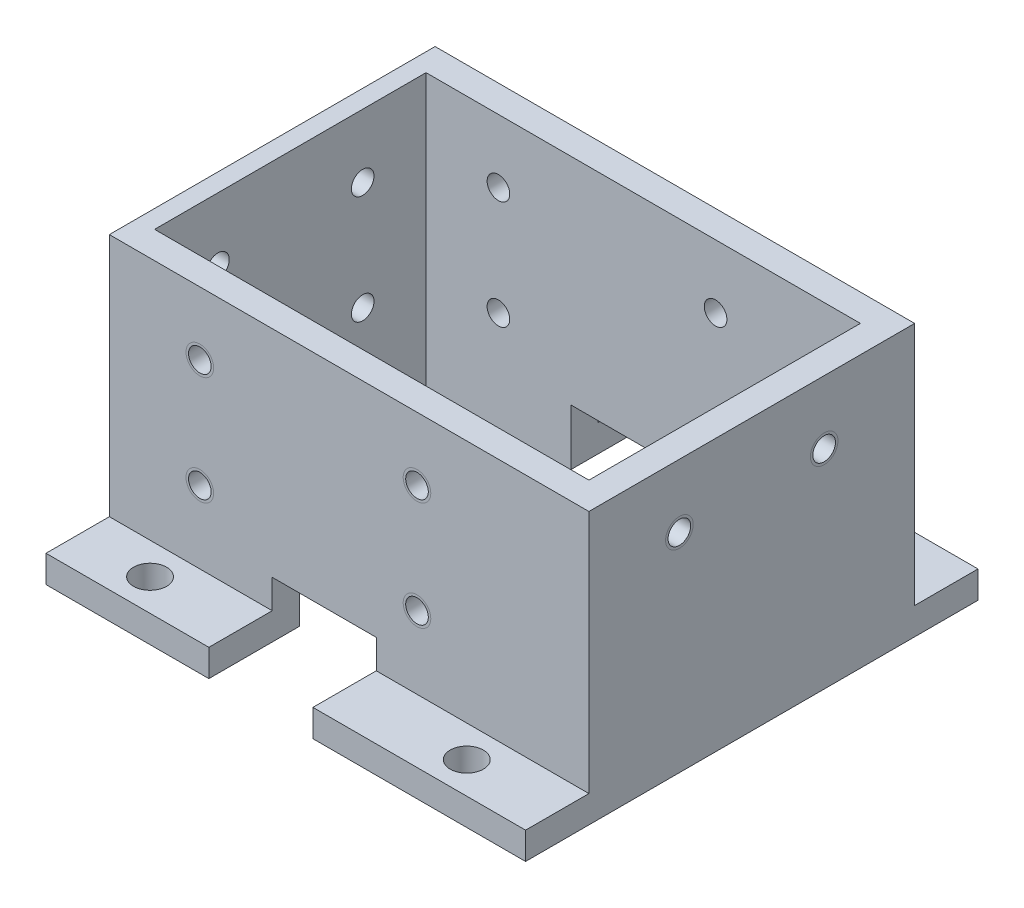
SolidWorks part; units mm, degrees
material "ABS"
ref_plane "Front Plane" through (0, 0, 0) normal (0, 0, 1) x (1, 0, 0)
ref_plane "Top Plane" through (0, 0, 0) normal (0, 1, 0) x (1, 0, 0)
ref_plane "Right Plane" through (0, 0, 0) normal (1, 0, 0) x (0, 0, -1)
sketch "Sketch1" plane through (0, 0, 0) normal (1, 0, 0) x (0, 0, -1)
  line L0 (0, 0) -> (0, 38)
  line L1 (0, 38) -> (36, 38)
  line L2 (36, 38) -> (36, 0)
  line L3 (36, 0) -> (0, 0)
  dimension "D1" = 38
  dimension "D2" = 36
extrude "Boss-Extrude2" add sketch "Sketch1" along normal blind 53
sketch "Sketch3" plane through (53, 0, 0) normal (1, 0, 0) x (0, 0, -1)
  line L0 (36, 0) -> (0, 0) construction
  line L1 (3, 0) -> (3, 35)
  line L2 (3, 35) -> (33, 35)
  line L3 (33, 35) -> (33, 0)
  line L4 (33, 0) -> (3, 0)
  line L5 (0, 38) -> (36, 38) construction
  line L6 (36, 38) -> (36, 0) construction
  line L7 (0, 0) -> (0, 38) construction
  dimension "D1" = 3
  dimension "D2" = 3
  dimension "D3" = 3
extrude "Cut-Extrude1" cut sketch "Sketch3" against normal blind 51
sketch "Sketch4" plane through (0, 0, 0) normal (0, 0, 1) x (1, 0, 0)
  line L0 (50, 0) -> (50, 30)
  line L1 (53, 0) -> (0, 0) construction
  line L2 (50, 30) -> (53, 30)
  line L3 (53, 38) -> (53, 0) construction
  line L4 (53, 30) -> (53, 0)
  line L5 (53, 0) -> (50, 0)
  dimension "D1" = 3
  dimension "D2" = 30
extrude "Boss-Extrude3" add sketch "Sketch4" against normal up to surface (33 mm away) up to face at (27.5, 17.5, -33)
sketch "Sketch5" plane through (0, 0, 0) normal (0, 0, 1) x (1, 0, 0)
  line L0 (53, 30) -> (0, 30)
  line L1 (53, 38) -> (53, 0) construction
  line L2 (0, 30) -> (0, 38)
  line L3 (53, 38) -> (0, 38) construction
  line L4 (0, 38) -> (53, 38)
  line L5 (53, 38) -> (53, 30)
  line L6 (53, 0) -> (0, 0) construction
  line L7 (0, 38) -> (0, 0) construction
  dimension "D1" = 30
  dimension "D2" = 0
extrude "Cut-Extrude2" cut sketch "Sketch5" against normal blind 52
sketch "Sketch6" plane through (0, 0, 0) normal (0, -1, 0) x (-1, 0, 0)
  line L0 (-53, 0) -> (-53, -7)
  line L1 (-53, -7) -> (0, -7)
  line L2 (0, -7) -> (0, 0)
  line L3 (0, 0) -> (-53, 0)
  line L4 (-53, 36) -> (-53, 43)
  line L5 (-53, 43) -> (0, 43)
  line L6 (0, 43) -> (0, 36)
  line L7 (0, 36) -> (-53, 36)
  dimension "D1" = 7
  dimension "D2" = 7
extrude "Boss-Extrude4" add sketch "Sketch6" against normal blind 3
sketch "Sketch8" plane through (0, 0, -43) normal (0, 0, -1) x (-1, 0, 0)
  line L0 (-29.5, 0) -> (-29.5, 3)
  line L1 (0, 0) -> (-53, 0) construction
  line L2 (-53, 3) -> (0, 3) construction
  line L3 (-29.5, 3) -> (-18, 3)
  line L4 (0, 3) -> (-53, 3) construction
  line L5 (-18, 3) -> (-18, 0)
  line L6 (-18, 0) -> (-29.5, 0)
  line L7 (-53, 3) -> (-53, 0) construction
  line L8 (0, 38) -> (0, 0) construction
  dimension "D1" = 23.5
  dimension "D2" = 18
extrude "Cut-Extrude4" cut sketch "Sketch8" against normal through all both and the other way through all
hole_wizard "M3 Tapped Hole1" positions "Sketch38" profile "Sketch35" tap size "M3" standard "AS"
sketch "Sketch38" plane through (0, 0, 0) normal (0, 0, 1) x (1, 0, 0)
  line L0 (0, 30) -> (0, 3) construction
  line L1 (18, 0) -> (0, 0) construction
  point P0 (10, 23)
  dimension "D1" = 10
  dimension "D2" = 23
sketch "Sketch35" plane through (10, 23, 0) normal (1, 0, 0) x (0, -1, 0)
  line L0 (0, 0) -> (0, 3)
  line L1 (0, 3) -> (1.25, 3)
  line L2 (1.25, 3) -> (1.25, 0.0024)
  line L3 (1.25, 0.0024) -> (1.525, 0)
  line L5 (1.525, 0) -> (0, 0)
  line L6 (-1.25, 0.0024) -> (-1.525, 0) construction
  line L11 (0, -6.35) -> (0, 107.95) construction
  dimension "Thru Tap Drill Dia." = 2.5
  dimension "Thru Tap Drill Depth" = 3
  dimension "Near C'Sink Dia." = 3.05
  dimension "Near C'Sink Angle" = 179
cosmetic thread "Hole Thread2" parameters "D2"=3
pattern_linear "LPattern1" count 2 spacing 24 along (1, 0, 0) count 2 spacing 12 along (0, -1, 0) of "M3 Tapped Hole1"
hole_wizard "M3 Tapped Hole2" positions "Sketch39" profile "Sketch40" tap size "M3" standard "AS"
sketch "Sketch39" plane through (0, 0, 0) normal (-1, 0, 0) x (0, 0, 1)
  line L0 (-36, 30) -> (0, 30) construction
  line L1 (-36, 3) -> (-36, 30) construction
  point P0 (-26, 23)
  dimension "D1" = 7
  dimension "D2" = 10
sketch "Sketch40" plane through (0, 23, -26) normal (0, 1, 0) x (0, 0, 1)
  line L0 (0, 0) -> (0, 2)
  line L1 (0, 2) -> (1.25, 2)
  line L2 (1.25, 2) -> (1.25, 0.0024)
  line L3 (1.25, 0.0024) -> (1.525, 0)
  line L5 (1.525, 0) -> (0, 0)
  line L6 (-1.25, 0.0024) -> (-1.525, 0) construction
  line L11 (0, -6.35) -> (0, 107.95) construction
  dimension "Thru Tap Drill Dia." = 2.5
  dimension "Thru Tap Drill Depth" = 2
  dimension "Near C'Sink Dia." = 3.05
  dimension "Near C'Sink Angle" = 179
cosmetic thread "Hole Thread3" parameters "D2"=3
pattern_linear "LPattern2" count 2 spacing 16 along (0, 0, 1) count 2 spacing 12 along (0, -1, 0) of "M3 Tapped Hole2"
hole_wizard "M3 Tapped Hole3" positions "Sketch41" profile "Sketch42" tap size "M3" standard "AS" end condition up to next
sketch "Sketch41" plane through (53, 0, 0) normal (1, 0, 0) x (0, 0, -1)
  line L0 (36, 30) -> (0, 30) construction
  line L1 (36, 3) -> (36, 30) construction
  point P0 (26, 23)
  dimension "D1" = 7
  dimension "D2" = 10
sketch "Sketch42" plane through (53, 23, -26) normal (0, 1, 0) x (0, 0, -1)
  line L0 (0, 0) -> (0, 3)
  line L1 (0, 3) -> (1.25, 3)
  line L2 (1.25, 3) -> (1.25, 0.0024)
  line L3 (1.25, 0.0024) -> (1.525, 0)
  line L5 (1.525, 0) -> (0, 0)
  line L6 (-1.25, 0.0024) -> (-1.525, 0) construction
  line L11 (0, -6.35) -> (0, 107.95) construction
  dimension "Thru Tap Drill Dia." = 2.5
  dimension "Thru Tap Drill Depth" = 3
  dimension "Near C'Sink Dia." = 3.05
  dimension "Near C'Sink Angle" = 179
cosmetic thread "Hole Thread4" parameters "D2"=3
pattern_linear "LPattern3" count 2 spacing 16 along (0, 0, 1) of "M3 Tapped Hole3"
hole_wizard "M3 Tapped Hole4" positions "Sketch43" profile "Sketch44" tap size "M3" standard "AS" end condition up to next
sketch "Sketch43" plane through (0, 0, -36) normal (0, 0, -1) x (-1, 0, 0)
  line L0 (0, 30) -> (-53, 30) construction
  line L1 (0, 3) -> (0, 30) construction
  point P0 (-10, 23)
  dimension "D1" = 7
  dimension "D2" = 10
sketch "Sketch44" plane through (10, 23, -36) normal (1, 0, 0) x (0, 1, 0)
  line L0 (0, 0) -> (0, 3)
  line L1 (0, 3) -> (1.25, 3)
  line L2 (1.25, 3) -> (1.25, 0.0024)
  line L3 (1.25, 0.0024) -> (1.525, 0)
  line L5 (1.525, 0) -> (0, 0)
  line L6 (-1.25, 0.0024) -> (-1.525, 0) construction
  line L11 (0, -6.35) -> (0, 107.95) construction
  dimension "Thru Tap Drill Dia." = 2.5
  dimension "Thru Tap Drill Depth" = 3
  dimension "Near C'Sink Dia." = 3.05
  dimension "Near C'Sink Angle" = 179
cosmetic thread "Hole Thread5" parameters "D2"=3
pattern_linear "LPattern4" count 2 spacing 24 along (1, 0, 0) count 2 spacing 12 along (0, -1, 0) of "M3 Tapped Hole4"
sketch "Sketch45" plane through (0, 3, 0) normal (0, 1, 0) x (1, 0, 0)
  line L0 (0, 36) -> (53, 36) construction
  line L1 (18, 43) -> (18, 36) construction
  circle A0 centre (8, 39.5) radius 1.8333
  dimension "D1" = 3.6667
  dimension "D2" = 3.5
  dimension "D3" = 10
extrude "Cut-Extrude5" cut sketch "Sketch45" against normal through all both and the other way through all
pattern_linear "LPattern5" count 2 spacing 35 along (1, 0, 0) count 2 spacing 43 along (0, 0, 1) of "Cut-Extrude5"
sketch "Sketch46" plane through (0, 0, -36) normal (0, 0, -1) x (-1, 0, 0)
  line L0 (-29.5, 3) -> (-29.5, 6.2)
  line L1 (-29.5, 6.2) -> (-18, 6.2)
  line L2 (-18, 6.2) -> (-18, 3)
  line L3 (-29.5, 3) -> (-18, 3)
  dimension "D1" = 3.2
extrude "Cut-Extrude6" cut sketch "Sketch46" against normal through all both and the other way through all
